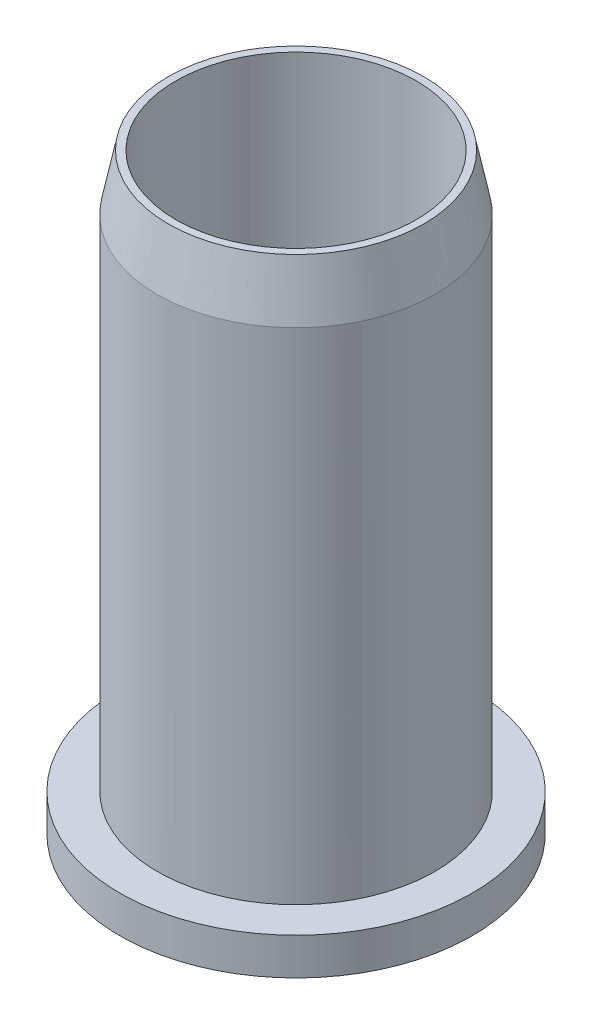
SolidWorks part; units mm, degrees
ref_plane "Front" through (0, 0, 0) normal (0, 0, 1) x (1, 0, 0)
ref_plane "Top" through (0, 0, 0) normal (0, 1, 0) x (1, 0, 0)
ref_plane "Right" through (0, 0, 0) normal (1, 0, 0) x (0, 0, -1)
sketch "草图1" plane through (0, 0, 0) normal (0, 0, 1) x (1, 0, 0)
  line L0 (3.25, 0) -> (3.25, 16) construction
  line L1 (3.25, 16) -> (3.75, 16)
  line L2 (3.75, 16) -> (3.75, 1)
  line L3 (3.75, 1) -> (4.76, 1)
  line L4 (4.76, 1) -> (4.76, 0)
  line L5 (4.76, 0) -> (3.25, 0)
  line L6 (3.25, 0) -> (3.25, 16)
  line L7 (0, 0) -> (0, 20.2238) construction
  point P12 (-4.6141, 10.472)
  dimension "D1" = 3.25
  dimension "D2" = 7.5
  dimension "D3" = 15
  dimension "D4" = 16
  dimension "D5" = 4.76
revolve "旋转1" add sketch "草图1" angle 360 about L7
chamfer "倒角1" distance 0.3 distance2 1.5 1 edges at (0, 16, -3.75)
